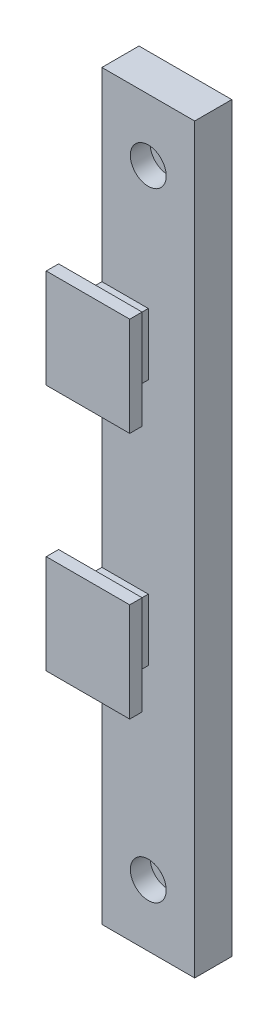
SolidWorks part; units mm, degrees
material "ABS"
ref_plane "前视基准面" through (0, 0, 0) normal (0, 0, 1) x (1, 0, 0)
ref_plane "上视基准面" through (0, 0, 0) normal (0, 1, 0) x (1, 0, 0)
ref_plane "右视基准面" through (0, 0, 0) normal (1, 0, 0) x (0, 0, -1)
other "Configuration Table"
sketch "草图1" plane through (0, 0, 0) normal (0, 0, 1) x (1, 0, 0)
  line L1 (-7.5, 60) -> (7.5, 60)
  line L2 (-7.5, 60) -> (-7.5, -60)
  line L3 (-7.5, -60) -> (7.5, -60)
  line L4 (7.5, 60) -> (7.5, -60)
  line L5 (-7.5, 60) -> (7.5, -60) construction
  line L6 (-7.5, -60) -> (7.5, 60) construction
  point P0 (0, 0)
  dimension "D1" = 120
  dimension "D2" = 15
extrude "凸台-拉伸1" add sketch "草图1" along normal blind 6
sketch "草图2" plane through (0, 0, 6) normal (0, 0, 1) x (1, 0, 0)
  line L0 (0, 0) -> (101.7242, 0) construction
  line L1 (0, 60) -> (0, -60) construction
  line L2 (7.5, 60) -> (-7.5, 60) construction
  line L3 (-7.5, -60) -> (7.5, -60) construction
  circle A0 centre (0, 50) radius 1.65
  circle A1 centre (0, -50) radius 1.65
  dimension "D1" = 50
  dimension "D2" = 3.3
extrude "切除-拉伸1" cut sketch "草图2" against normal through all
sketch "草图3" plane through (0, 0, 0) normal (0, 0, -1) x (-1, 0, 0)
  line L0 (0, 50) -> (0, -50) construction
  line L2 (-2.9, 2.46) -> (2.9, 2.46)
  line L3 (-2.9, 2.46) -> (-2.9, -13.34)
  line L4 (-2.9, -13.34) -> (2.9, -13.34)
  line L5 (2.9, 2.46) -> (2.9, -13.34)
  circle A0 centre (0, -0.44) radius 2.9 construction
  circle A1 centre (0, -10.44) radius 2.9 construction
  circle A2 centre (0, 50) radius 1.65 construction
  dimension "D1" = 50.44
  dimension "D2" = 10
  dimension "D3" = 5.8
extrude "切除-拉伸2" cut sketch "草图3" against normal blind 3.1
sketch "草图4" plane through (0, 0, 0) normal (0, 0, -1) x (-1, 0, 0)
  line L1 (0, 0) -> (0, 14.4376) construction
  line L2 (-2.9, 2.46) -> (0, 5.36)
  line L3 (0, 5.36) -> (2.9, 2.46)
  line L4 (2.9, 2.46) -> (-2.9, 2.46) construction
  line L5 (-2.9, 2.46) -> (2.9, 2.46)
  dimension "D1" = 45
extrude "切除-拉伸3" cut sketch "草图4" against normal up to surface (3.1 mm away) up to face at (0, -5.44, 3.1)
sketch "草图5" plane through (0, 0, 6) normal (0, 0, 1) x (1, 0, 0)
  circle A0 centre (0, 50) radius 2.9
  circle A1 centre (0, -50) radius 2.9
  dimension "D1" = 5.8
extrude "切除-拉伸4" cut sketch "草图5" against normal blind 3.2
sketch "草图6" plane through (0, 0, 6) normal (0, 0, 1) x (1, 0, 0)
  line L0 (-7.5, 60) -> (-7.5, -60) construction
  line L4 (7.5, -45.7517) -> (7.5, -60) construction
  line L7 (-7.5, -20) -> (0, -20)
  line L8 (-7.5, -20) -> (-7.5, -10)
  line L9 (-7.5, -10) -> (0, -10)
  line L10 (0, -20) -> (0, -10)
  line L11 (0, 20) -> (-7.5, 20)
  line L12 (0, 20) -> (0, 30)
  line L13 (0, 30) -> (-7.5, 30)
  line L14 (-7.5, 20) -> (-7.5, 30)
  point P0 (0, -50)
  point P3 (-7.5, -25.9625)
  point P17 (-17.6539, -26.4614)
  point P18 (1.1367, 12.0893)
  dimension "D1" = 10
  dimension "D2" = 10
  dimension "D3" = 30
  dimension "D4" = 30
extrude "凸台-拉伸2" add sketch "草图6" along normal blind 4
sketch "草图7" plane through (0, 0, 10) normal (0, 0, 1) x (1, 0, 0)
  line L8 (3, 17) -> (3, 33)
  line L9 (3, 33) -> (-10.5, 33)
  line L10 (-10.5, 33) -> (-10.5, 17)
  line L11 (-10.5, 17) -> (3, 17)
  line L12 (3, 17) -> (3, 33)
  line L13 (3, 33) -> (-10.5, 33)
  line L14 (-10.5, 33) -> (-10.5, 17)
  line L15 (-10.5, 17) -> (3, 17)
  line L20 (-10.5, -7) -> (-10.5, -23)
  line L21 (-10.5, -23) -> (3, -23)
  line L22 (3, -23) -> (3, -7)
  line L23 (3, -7) -> (-10.5, -7)
  line L24 (-10.5, -7) -> (-10.5, -23)
  line L25 (-10.5, -23) -> (3, -23)
  line L26 (3, -23) -> (3, -7)
  line L27 (3, -7) -> (-10.5, -7)
  dimension "D1" = 3
  dimension "D2" = 3
extrude "凸台-拉伸3" add sketch "草图7" along normal blind 2
